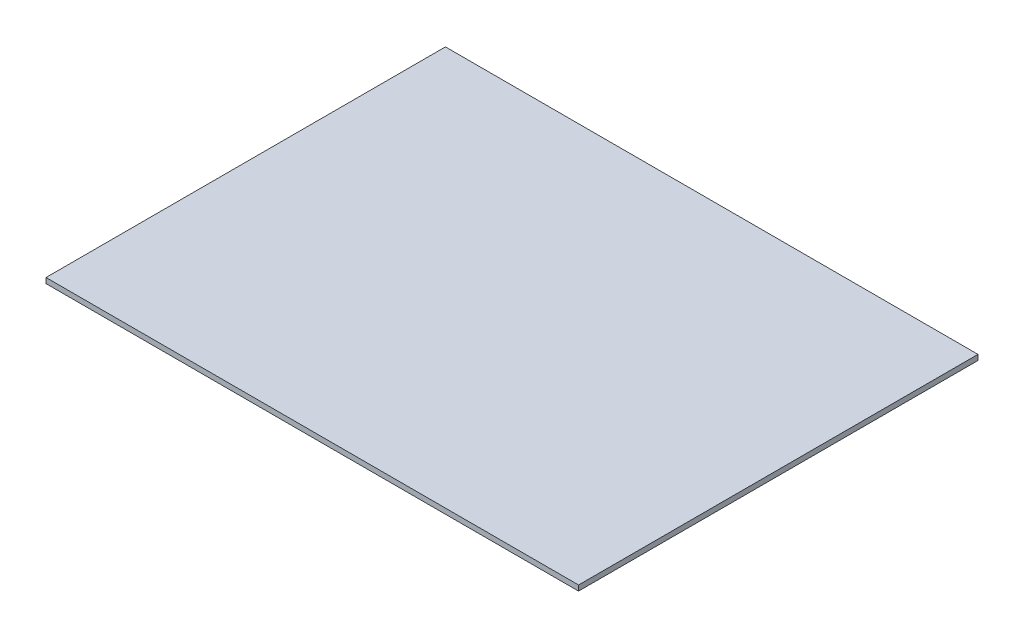
SolidWorks part; units mm, degrees
ref_plane "Front Plane" through (0, 0, 0) normal (0, 0, 1) x (1, 0, 0)
ref_plane "Top Plane" through (0, 0, 0) normal (0, 1, 0) x (1, 0, 0)
ref_plane "Right Plane" through (0, 0, 0) normal (1, 0, 0) x (0, 0, -1)
sketch "Sketch1" plane through (0, 0, 0) normal (0, 1, 0) x (1, 0, 0)
  line L1 (0, 0) -> (200, 0)
  line L2 (0, 0) -> (0, 150)
  line L3 (0, 150) -> (200, 150)
  line L4 (200, 0) -> (200, 150)
  dimension "D1" = 150
  dimension "D2" = 200
extrude "Boss-Extrude1" add sketch "Sketch1" along normal blind 2
